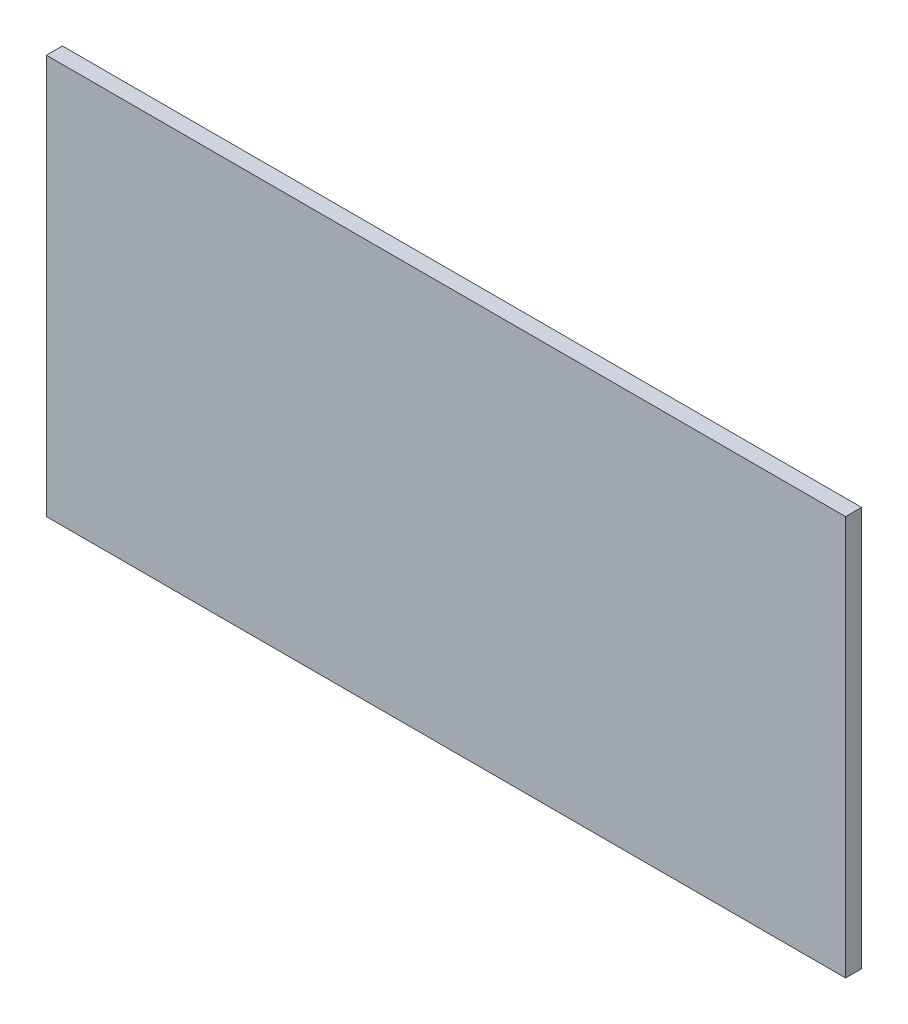
SolidWorks part; units mm, degrees
material "Лист 4,0 ГОСТ 19903-2015 / Ст3сп ГОСТ 14637-89"
ref_plane "Спереди" through (0, 0, 0) normal (0, 0, 1) x (1, 0, 0)
ref_plane "Сверху" through (0, 0, 0) normal (0, 1, 0) x (1, 0, 0)
ref_plane "Справа" through (0, 0, 0) normal (1, 0, 0) x (0, 0, -1)
sketch "Эскиз1" plane through (0, 0, 0) normal (0, 0, 1) x (1, 0, 0)
  line L1 (-100, -50) -> (100, -50)
  line L2 (-100, -50) -> (-100, 50)
  line L3 (-100, 50) -> (100, 50)
  line L4 (100, -50) -> (100, 50)
extrude "Бобышка-Вытянуть1" add sketch "Эскиз1" along normal blind 4
